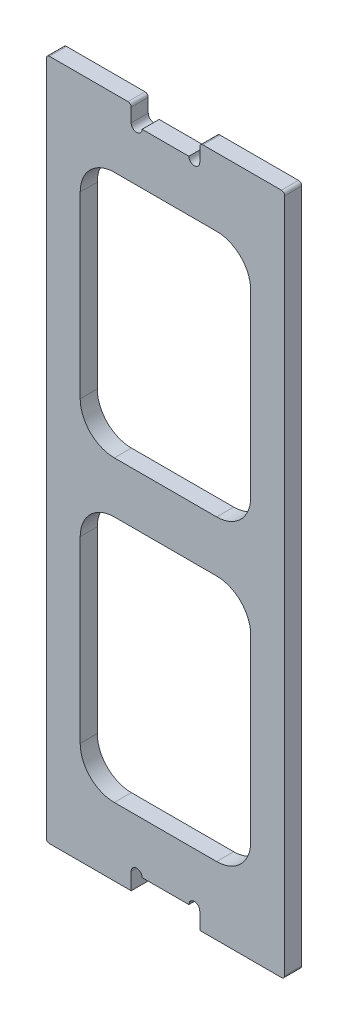
SolidWorks part; units mm, degrees
material "Hexcel AS4C (3000 丝)"
ref_plane "前视基准面" through (0, 0, 0) normal (0, 0, 1) x (1, 0, 0)
ref_plane "上视基准面" through (0, 0, 0) normal (0, 1, 0) x (1, 0, 0)
ref_plane "右视基准面" through (0, 0, 0) normal (1, 0, 0) x (0, 0, -1)
other "Configuration Table"
sketch "草图1" plane through (0, 0, 0) normal (0, 0, 1) x (1, 0, 0)
  line L1 (0, 0) -> (70, 0)
  line L2 (0, 0) -> (0, 190)
  line L3 (0, 190) -> (70, 190)
  line L4 (70, 0) -> (70, 190)
  line L5 (45, 0) -> (70, 0)
  line L6 (45, 0) -> (45, -5)
  line L7 (45, -5) -> (70, -5)
  line L8 (70, 0) -> (70, -5)
  line L9 (0, 0) -> (25, 0)
  line L10 (0, 0) -> (0, -5)
  line L11 (0, -5) -> (25, -5)
  line L12 (25, 0) -> (25, -5)
  line L13 (70, 190) -> (45, 190)
  line L14 (70, 190) -> (70, 195)
  line L15 (70, 195) -> (45, 195)
  line L16 (45, 190) -> (45, 195)
  line L17 (0, 190) -> (25, 190)
  line L18 (0, 190) -> (0, 195)
  line L19 (0, 195) -> (25, 195)
  line L20 (25, 190) -> (25, 195)
  dimension "D1" = 70
  dimension "D2" = 190
  dimension "D3" = 25
  dimension "D4" = 25
  dimension "D5" = 5
  dimension "D6" = 5
  dimension "D7" = 25
  dimension "D8" = 25
  dimension "D9" = 5
  dimension "D10" = 5
extrude "凸台-拉伸1" add sketch "草图1" along normal blind 5 contours L16 L3 L14 L15 | L1 L4 L3 L2 | L3 L20 L19 L18 | L8 L1 L6 L7 | L12 L1 L10 L11
sketch "草图2" plane through (0, 0, 5) normal (0, 0, 1) x (1, 0, 0)
  line L0 (25, 0) -> (45, 0) construction
  line L1 (45, 0) -> (45, -5) construction
  line L2 (25, 0) -> (25, -5) construction
  line L3 (25, 190) -> (45, 190) construction
  line L4 (25, 190) -> (25, 195) construction
  line L5 (45, 190) -> (45, 195) construction
  circle A0 centre (43.45, 0) radius 1.55
  circle A1 centre (26.55, 0) radius 1.55
  circle A2 centre (43.45, 190) radius 1.55
  circle A3 centre (26.55, 190) radius 1.55
  dimension "D4" = 3.1
extrude "切除-拉伸1" cut sketch "草图2" against normal blind 5
sketch "草图3" plane through (0, 0, 5) normal (0, 0, 1) x (1, 0, 0)
  line L0 (-53.1567, 95) -> (111.5166, 95) construction
  line L1 (35, -9.6754) -> (35, 200.1889) construction
  line L2 (70, -5) -> (70, 195) construction
  line L3 (0, -5) -> (0, 195) construction
  line L4 (45, -5) -> (70, -5) construction
  line L5 (70, 195) -> (45, 195) construction
  line L6 (28.1, 0) -> (41.9, 0) construction
  line L7 (10, 87.5) -> (60, 87.5)
  line L8 (10, 87.5) -> (10, 15)
  line L9 (10, 15) -> (60, 15)
  line L10 (60, 87.5) -> (60, 15)
  line L11 (10, 175) -> (60, 175)
  line L12 (10, 102.5) -> (60, 102.5)
  line L13 (10, 102.5) -> (10, 175)
  line L14 (60, 102.5) -> (60, 175)
  dimension "D1" = 7.5
  dimension "D2" = 10
  dimension "D3" = 10
  dimension "D4" = 15
extrude "切除-拉伸2" cut sketch "草图3" against normal up to surface (5 mm away) up to face at (35, 95, 0)
fillet "圆角1" radius 10 8 edges at (10, 15, 2.5) (60, 15, 2.5) (60, 87.5, 2.5) (10, 87.5, 2.5) (10, 102.5, 2.5) (60, 102.5, 2.5) (10, 175, 2.5) (60, 175, 2.5)
fillet "圆角2" radius 1 6 edges at (25, 195, 2.5) (45, 195, 2.5) (0, 195, 2.5) (70, 195, 2.5) (0, -5, 2.5) (70, -5, 2.5)
other "移动面1" face at (69.6036, -4.6036, 2.5) face at (57, -5, 2.5) face at (45, -2.5, 2.5) face at (43.45, 0.775, 2.5) face at (25, -2.5, 2.5) face at (26.55, 0.775, 2.5) face at (13, -5, 2.5) face at (0.3964, -4.6036, 2.5) face at (0, 95, 2.5) face at (0.3964, 194.6036, 2.5) face at (12.5, 195, 2.5) face at (24.6036, 194.6036, 2.5) face at (25, 192, 2.5) face at (26.55, 189.225, 2.5) face at (43.45, 189.225, 2.5) face at (45, 192, 2.5) face at (45.3964, 194.6036, 2.5) face at (57.5, 195, 2.5) face at (69.6036, 194.6036, 2.5) face at (70, 95, 2.5) parameters "D1"=0.05
